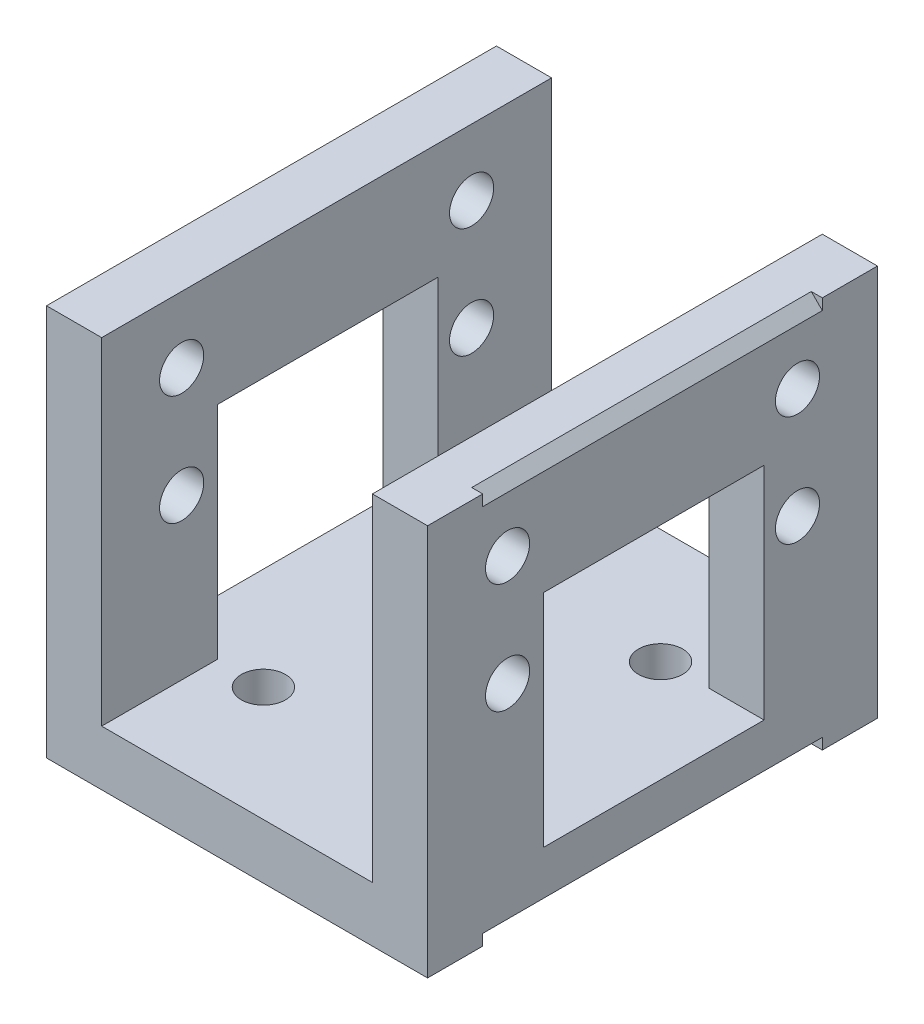
SolidWorks part; units mm, degrees
material "PEI"
ref_plane "前视基准面" through (0, 0, 0) normal (0, 0, 1) x (1, 0, 0)
ref_plane "上视基准面" through (0, 0, 0) normal (0, 1, 0) x (1, 0, 0)
ref_plane "右视基准面" through (0, 0, 0) normal (1, 0, 0) x (0, 0, -1)
other "Configuration Table"
sketch "草图1" plane through (0, 0, 0) normal (0, 0, 1) x (1, 0, 0)
  line L0 (0, 0) -> (58.1502, 0) construction
  line L5 (0, 0) -> (0, 35.5)
  line L6 (0, 0) -> (34.54, 0)
  line L7 (34.54, 0) -> (34.54, 35.5)
  line L8 (29.54, 5) -> (29.54, 35.5)
  line L9 (5, 5) -> (29.54, 5)
  line L10 (5, 5) -> (5, 35.5)
  line L11 (0, 35.5) -> (5, 35.5)
  line L12 (29.54, 35.5) -> (34.54, 35.5)
  dimension "D1" = 35.5
  dimension "D2" = 34.54
  dimension "D3" = 5
extrude "凸台-拉伸2" add sketch "草图1" along normal blind 34.78
sketch "草图2" plane through (34.54, 0, 0) normal (1, 0, 0) x (0, 0, -1)
  line L1 (-27.28, 5) -> (-7.28, 5)
  line L2 (-27.28, 5) -> (-27.28, 25)
  line L3 (-27.28, 25) -> (-7.28, 25)
  line L4 (-7.28, 5) -> (-7.28, 25)
  line L5 (-34.78, 0) -> (-34.78, 35.5) construction
  line L7 (-34.78, 0) -> (0, 0) construction
  dimension "D1" = 20
  dimension "D2" = 20
  dimension "D3" = 7.5
  dimension "D4" = 5
extrude "切除-拉伸1" cut sketch "草图2" against normal up to surface (34.54 mm away) up to face at (0, 17.75, 17.39)
chamfer "倒角1" distance 1 angle 45 9 edges at (34.54, 0, 17.39) (34.54, 17.75, 34.78) (34.54, 35.5, 17.39) (34.54, 17.75, 0) (0, 17.75, 0) (0, 17.75, 34.78) (17.27, 0, 0) (0, 0, 17.39) (17.27, 0, 34.78)
sketch "草图3" plane through (34.54, 0, 0) normal (1, 0, 0) x (0, 0, -1)
  line L0 (-33.78, 24.5) -> (-27.28, 24.5)
  line L1 (-33.78, 34.5) -> (-27.28, 34.5)
  line L2 (-33.78, 34.5) -> (-33.78, 5)
  line L3 (-33.78, 5) -> (-27.28, 5)
  line L4 (-27.28, 34.5) -> (-27.28, 5)
  line L5 (-33.78, 34.5) -> (-27.28, 24.5)
  line L6 (-27.28, 34.5) -> (-33.78, 24.5)
  line L7 (-1, 34.5) -> (-33.78, 34.5) construction
  line L8 (-1, 34.5) -> (-33.78, 34.5)
  line L9 (-17.39, 34.5) -> (-17.39, 26.7348) construction
  circle A0 centre (-30.53, 29.5) radius 2
  circle A1 centre (-4.25, 29.5) radius 2
  circle A2 centre (-4.25, 19.5) radius 2
  circle A3 centre (-30.53, 19.5) radius 2
  dimension "D2" = 4
  dimension "D1" = 10
extrude "切除-拉伸2" cut sketch "草图3" against normal up to surface (34.54 mm away) contours A3 | A2 | A1 | L5 A0 L6 | L6 A0 L5 | L5 A0 L6 | L6 A0 L5
sketch "草图4" plane through (0, 0, 0) normal (0, -1, 0) x (1, 0, 0)
  line L0 (-4.1213, 17.39) -> (38.0146, 17.39) construction
  line L1 (17.27, -1.7129) -> (17.27, 36.1944) construction
  line L2 (9.27, 7.39) -> (9.27, 27.39) construction
  line L3 (9.27, 27.39) -> (25.27, 27.39) construction
  line L5 (9.27, 7.39) -> (25.27, 7.39) construction
  line L6 (1, 1) -> (33.54, 1)
  line L7 (33.54, 1) -> (33.54, 33.78)
  line L8 (33.54, 33.78) -> (1, 33.78)
  line L9 (1, 33.78) -> (1, 1)
  line L10 (1, 1) -> (33.54, 1)
  line L11 (33.54, 1) -> (33.54, 33.78)
  line L12 (33.54, 33.78) -> (1, 33.78)
  line L13 (1, 33.78) -> (1, 1)
  line L15 (25.27, 7.39) -> (25.27, 27.39) construction
  circle A0 centre (9.27, 27.39) radius 2
  circle A1 centre (9.27, 7.39) radius 2
  circle A2 centre (25.27, 7.39) radius 2
  circle A3 centre (25.27, 27.39) radius 2
  point P7 (1, 17.39)
  point P9 (17.27, 1)
  dimension "D5" = 4
  dimension "D6" = 4
  dimension "D7" = 4
  dimension "D8" = 4
  dimension "D1" = 0
  dimension "D2" = 16
  dimension "D3" = 10
  dimension "D4" = 8
  dimension "D9" = 10
extrude "切除-拉伸3" cut sketch "草图4" against normal up to surface (5 mm away) contours A0 | A3 | A2 | A1 up to face at (17.27, 5, 17.3167)
ref_plane "基准面1" through (0, 0, 17.39) normal (0, 0, 1) x (1, 0, 0)
sketch "草图8" plane through (0, 0, 34.78) normal (0, 0, 1) x (1, 0, 0)
  line L0 (34.54, 34.5) -> (34.54, 1) construction
  line L1 (33.54, 0) -> (1, 0) construction
  line L2 (33.54, 35.5) -> (29.54, 35.5) construction
  line L3 (0, 35.5) -> (1, 35.5) construction
  line L4 (5, 35.5) -> (1, 35.5) construction
  line L5 (0, 1) -> (0, 35.5) construction
  line L6 (34.54, 34.5) -> (34.54, 1)
  line L7 (33.54, 0) -> (1, 0)
  line L8 (33.54, 35.5) -> (29.54, 35.5)
  line L9 (0, 35.5) -> (1, 35.5)
  line L10 (5, 35.5) -> (1, 35.5)
  line L11 (0, 1) -> (0, 35.5)
  line L12 (29.54, 35.5) -> (29.54, 5) construction
  line L13 (0, 35.5) -> (5, 35.5)
  line L14 (0, 35.5) -> (0, 0)
  line L15 (0, 0) -> (34.54, 0)
  line L16 (34.54, 35.5) -> (34.54, 0)
  line L17 (29.54, 5) -> (5, 5) construction
  line L18 (5, 5) -> (5, 35.5) construction
  line L19 (29.54, 35.5) -> (29.54, 5)
  line L20 (29.54, 5) -> (5, 5)
  line L21 (5, 5) -> (5, 35.5)
  line L22 (29.54, 35.5) -> (34.54, 35.5)
  line M9 (1, 1) -> (33.54, 1)
  line M10 (33.54, 1) -> (33.54, 35.5)
  line M11 (33.54, 35.5) -> (29.54, 35.5)
  line M12 (29.54, 35.5) -> (29.54, 5)
  line M13 (29.54, 5) -> (5, 5)
  line M14 (5, 5) -> (5, 35.5)
  line M15 (5, 35.5) -> (1, 35.5)
  line M16 (1, 35.5) -> (1, 1)
extrude "凸台-拉伸3" add sketch "草图8" along normal blind 3 and the other way blind 2 contours M16 M9 M10 M11 M12 M13 M14 M15 | L22 L9 L11 L14 L15 L7 L16 L6 M10 M9 M16
mirror "镜向1" about plane through (0, 0, 17.39) normal (0, 0, 1) of "凸台-拉伸3"
equation "\"D2@草图1\"= \"肩_连接件长度\""
equation "\"肩距\"= 110"
equation "\"肩_连接件长度\"= \"肩距\" - 2 * \"安装距_肩关节\""
equation "\"安装距_肩关节\"= 37.73"
